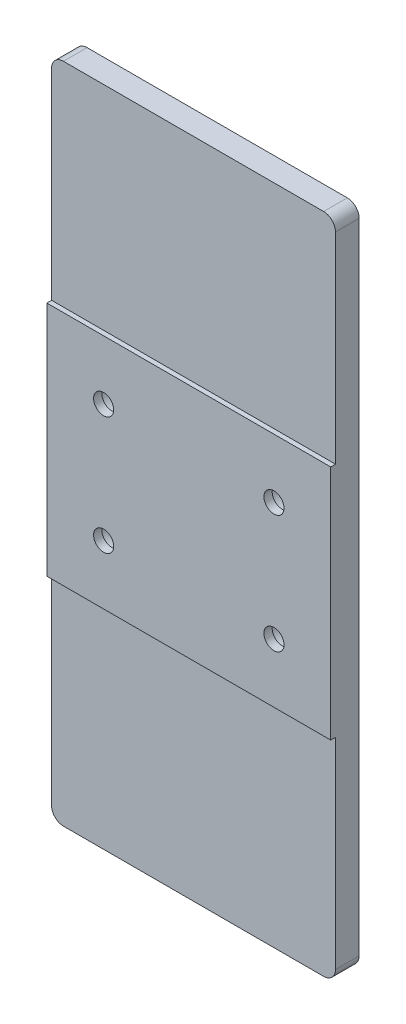
SolidWorks part; units mm, degrees
ref_plane "前视基准面" through (0, 0, 0) normal (0, 0, 1) x (1, 0, 0)
ref_plane "上视基准面" through (0, 0, 0) normal (0, 1, 0) x (1, 0, 0)
ref_plane "右视基准面" through (0, 0, 0) normal (1, 0, 0) x (0, 0, -1)
other "Configuration Table"
sketch "草图1" plane through (0, 0, 0) normal (0, 0, 1) x (1, 0, 0)
  line L0 (0, 0) -> (116.2084, 0) construction
  line L1 (-60, 140) -> (60, 140)
  line L2 (-60, 140) -> (-60, -140)
  line L3 (-60, -140) -> (60, -140)
  line L4 (60, 140) -> (60, -140)
  line L5 (0, 0) -> (0, 132.4863) construction
  line L6 (-12.9778, 110) -> (34.9174, 110) construction
  circle A0 centre (36, 25) radius 4.25
  circle A1 centre (36, -25) radius 4.25
  circle A2 centre (-36, -25) radius 4.25
  circle A3 centre (-36, 25) radius 4.25
  circle A12 centre (15, 125) radius 4.25 construction
  circle A14 centre (15, 95) radius 4.25 construction
  circle A15 centre (-15, 95) radius 4.25 construction
  circle A16 centre (-15, 125) radius 4.25 construction
  circle A17 centre (-15, -125) radius 4.25 construction
  circle A18 centre (15, -125) radius 4.25 construction
  circle A19 centre (-15, -95) radius 4.25 construction
  circle A20 centre (15, -95) radius 4.25 construction
  dimension "D2" = 8.5
  dimension "D12" = 8.5
  dimension "D1" = 280
  dimension "D3" = 72
  dimension "D4" = 50
  dimension "D5" = 120
  dimension "D11" = 110
  dimension "D13" = 15
  dimension "D14" = 15
extrude "凸台-拉伸1" add sketch "草图1" along normal blind 10
fillet "圆角1" radius 5 4 edges at (60, -140, 5) (-60, -140, 5) (-60, 140, 5) (60, 140, 5)
sketch "草图2" plane through (0, 0, 10) normal (0, 0, 1) x (1, 0, 0)
  line L6 (-60, -50) -> (-60, 50)
  line L7 (-60, 135) -> (-60, -135) construction
  line L8 (-60, 50) -> (60, 50)
  line L9 (60, -135) -> (60, 135) construction
  line L10 (60, 50) -> (60, -50)
  line L11 (60, -50) -> (-60, -50)
  line L12 (0, 0) -> (150.9983, 0) construction
  dimension "D1" = 100
extrude "凸台-拉伸2" add sketch "草图2" along normal blind 2
sketch "草图3" plane through (0, 0, 0) normal (0, 0, -1) x (-1, 0, 0)
  circle A0 centre (-36, -25) radius 4.25 construction
  circle A1 centre (-36, 25) radius 4.25 construction
  circle A2 centre (36, 25) radius 4.25 construction
  circle A3 centre (36, -25) radius 4.25 construction
  circle A4 centre (-36, -25) radius 4.25
  circle A5 centre (-36, 25) radius 4.25
  circle A6 centre (36, 25) radius 4.25
  circle A7 centre (36, -25) radius 4.25
extrude "切除-拉伸1" cut sketch "草图3" against normal blind 35
sketch "草图5" plane through (0, 0, 0) normal (0, 0, -1) x (-1, 0, 0)
  circle A0 centre (36, 25) radius 7
  circle A1 centre (36, -25) radius 7
  circle A2 centre (-36, -25) radius 7
  circle A3 centre (-36, 25) radius 7
  dimension "D1" = 14
extrude "切除-拉伸3" cut sketch "草图5" against normal blind 8.5
